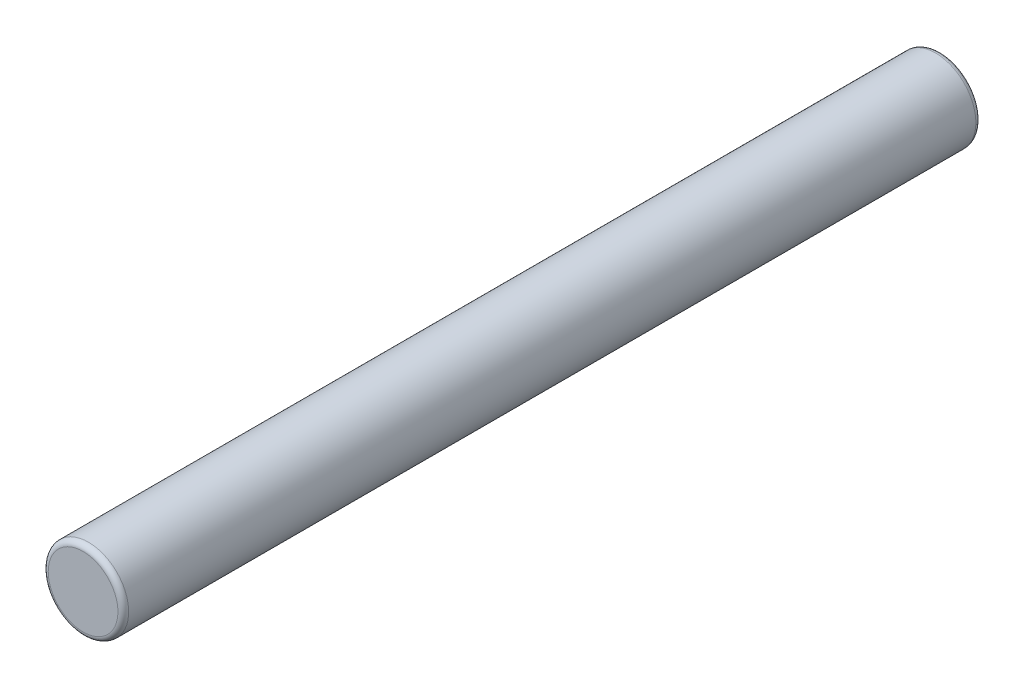
SolidWorks part; units mm, degrees
material "Liga 1060"
ref_plane "Plano frontal" through (0, 0, 0) normal (0, 0, 1) x (1, 0, 0)
ref_plane "Plano superior" through (0, 0, 0) normal (0, 1, 0) x (1, 0, 0)
ref_plane "Plano direito" through (0, 0, 0) normal (1, 0, 0) x (0, 0, -1)
ref_plane "Plano1" through (0, 0, 0) normal (0, -1, 0) x (1, 0, 0)
sketch "Esboço1" plane through (0, 0, 0) normal (0, -1, 0) x (1, 0, 0)
  line L0 (1.3, 16) -> (0, 16)
  line L1 (0, 16) -> (0, -16)
  line L2 (0, -16) -> (1.3, -16)
  line L3 (1.5, -15.8) -> (1.5, 15.8)
  line L4 (0, 16) -> (0, -16) construction
  arc A0 (1.3, -16) -> (1.5, -15.8) centre (1.3, -15.8) ccw
  arc A1 (1.5, 15.8) -> (1.3, 16) centre (1.3, 15.8) ccw
revolve "Revolução1" add sketch "Esboço1" angle 360 about L4
